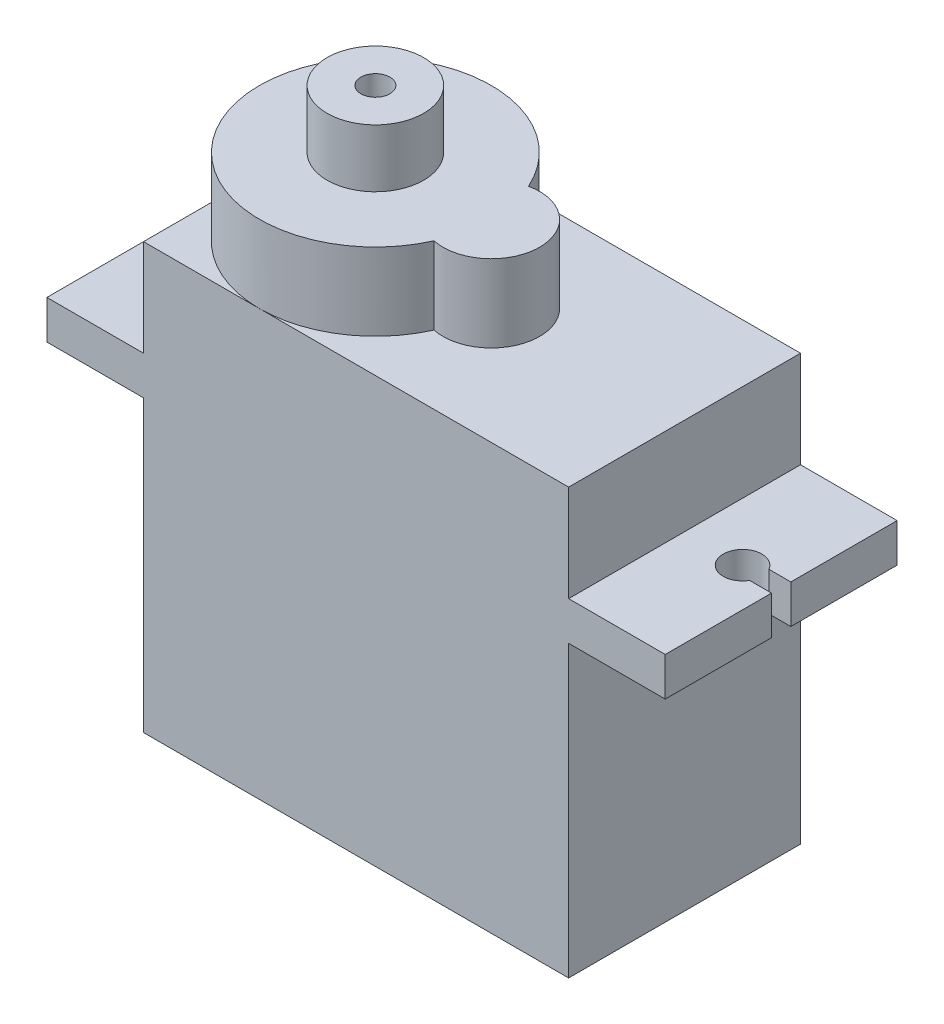
SolidWorks part; units mm, degrees
ref_plane "Front Plane" through (0, 0, 0) normal (0, 0, 1) x (1, 0, 0)
ref_plane "Top Plane" through (0, 0, 0) normal (0, 1, 0) x (1, 0, 0)
ref_plane "Right Plane" through (0, 0, 0) normal (1, 0, 0) x (0, 0, -1)
sketch "Sketch1" plane through (0, 0, 0) normal (0, 1, 0) x (1, 0, 0)
  line L1 (-11, 6) -> (11, 6)
  line L2 (-11, 6) -> (-11, -6)
  line L3 (-11, -6) -> (11, -6)
  line L4 (11, 6) -> (11, -6)
  line L5 (-11, 6) -> (11, -6) construction
  line L6 (-11, -6) -> (11, 6) construction
  point P0 (0, 0)
  dimension "D1" = 22
  dimension "D2" = 12
extrude "Boss-Extrude1" add sketch "Sketch1" along normal blind 22
sketch "Sketch2" plane through (0, 22, 0) normal (0, 1, 0) x (1, 0, 0)
  line L0 (11, 6) -> (-11, 6) construction
  line L1 (-11, 6) -> (-11, -6) construction
  line L2 (-11, -6) -> (11, -6) construction
  line L3 (0, 0) -> (2, 0) construction
  arc A0 (0.4792, 2.4451) -> (0.4792, -2.4451) centre (-5, 0) ccw
  arc A1 (0.4792, -2.4451) -> (0.4792, 2.4451) centre (1, 0) ccw
  dimension "D1" = 5
  dimension "D2" = 12
extrude "Boss-Extrude2" add sketch "Sketch2" along normal blind 4
sketch "Sketch3" plane through (0, 0, 6) normal (0, 0, 1) x (1, 0, 0)
  line L0 (11, 22) -> (11, 0) construction
  line L1 (11, 17) -> (16, 17)
  line L2 (11, 17) -> (11, 15)
  line L3 (11, 15) -> (16, 15)
  line L4 (16, 17) -> (16, 15)
  line L5 (-11, 0) -> (11, 0) construction
  dimension "D1" = 5
  dimension "D2" = 2
  dimension "D3" = 15
extrude "Boss-Extrude3" add sketch "Sketch3" against normal up to surface (12 mm away) up to face at (-1, 13.2, -6)
sketch "Sketch4" plane through (0, 17, 0) normal (0, 1, 0) x (1, 0, 0)
  line L0 (14.866, 0.5) -> (16, 0.5)
  line L1 (16, 6) -> (16, -6) construction
  line L2 (16, 0.5) -> (16, -0.5)
  line L3 (16, -0.5) -> (14.866, -0.5)
  line L4 (16, 0) -> (15, 0) construction
  line L5 (11, -6) -> (11, 6) construction
  line L6 (13, 0) -> (11, 0) construction
  arc A0 (14.866, 0.5) -> (14.866, -0.5) centre (14, 0) ccw
  point P6 (0, 0)
  dimension "D1" = 2
  dimension "D2" = 2
  dimension "D3" = 1
  dimension "D4" = 0.5
extrude "Cut-Extrude1" cut sketch "Sketch4" against normal up to next
mirror "Mirror1" about plane through (0, 0, 0) normal (1, 0, 0) of "Boss-Extrude3", "Cut-Extrude1"
sketch "Sketch5" plane through (0, 26, 0) normal (0, 1, 0) x (1, 0, 0)
  line L0 (-5, 6) -> (-5, -6) construction
  line L1 (-5, 6) -> (-11, 6) construction
  circle A0 centre (-5, 0) radius 2.5
  circle A1 centre (-5, 0) radius 0.75
  arc A2 (0.4792, 2.4451) -> (0.4792, -2.4451) centre (-5, 0) ccw construction
  point P11 (0, 0)
  point P12 (-6.7184, 1.1274)
  point P13 (-5, 0)
  dimension "D1" = 5
  dimension "D2" = 1.5
extrude "Boss-Extrude4" add sketch "Sketch5" along normal blind 3
equation "\"D4@Sketch4\"=\"D3@Sketch4\"/2"
